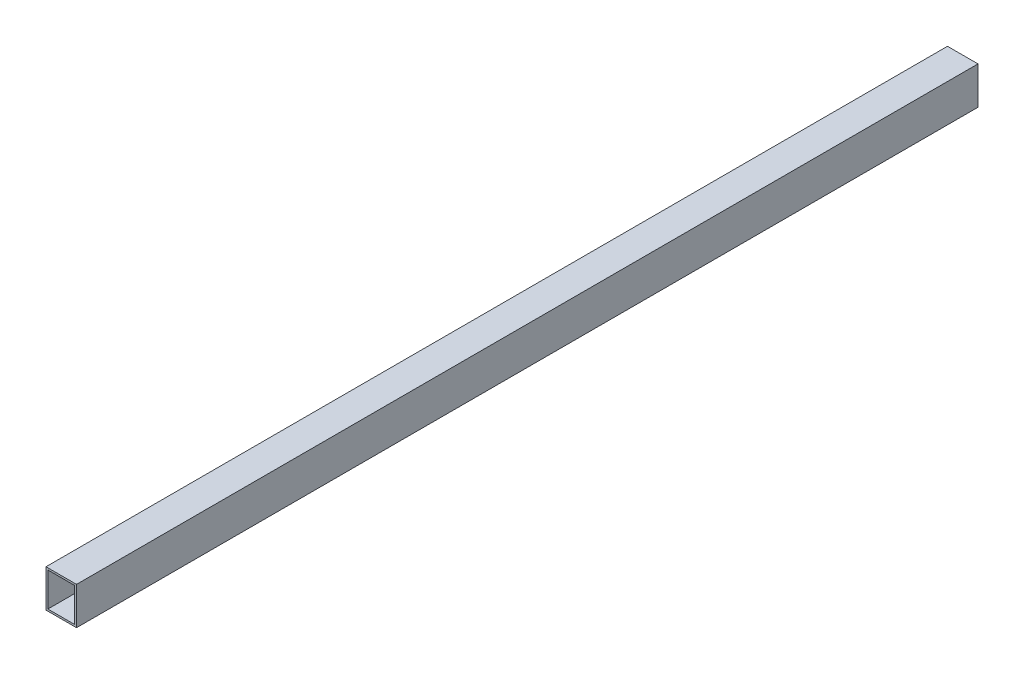
SolidWorks part; units mm, degrees
material "1060 Alloy"
ref_plane "Front Plane" through (0, 0, 0) normal (0, 0, 1) x (1, 0, 0)
ref_plane "Top Plane" through (0, 0, 0) normal (0, 1, 0) x (1, 0, 0)
ref_plane "Right Plane" through (0, 0, 0) normal (1, 0, 0) x (0, 0, -1)
sketch "Sketch4" plane through (0, 0, 0) normal (1, 0, 0) x (0, 0, -1)
  line L1 (-334, -52) -> (885.2, -52)
  line L2 (-334, -52) -> (-334, -102.8)
  line L3 (-334, -102.8) -> (885.2, -102.8)
  line L4 (885.2, -52) -> (885.2, -102.8)
  dimension "D1" = 1219.2
  dimension "D2" = 50.8
extrude "Boss-Extrude2" add sketch "Sketch4" against normal blind 41.275
shell "Shell7" thickness 2.54
